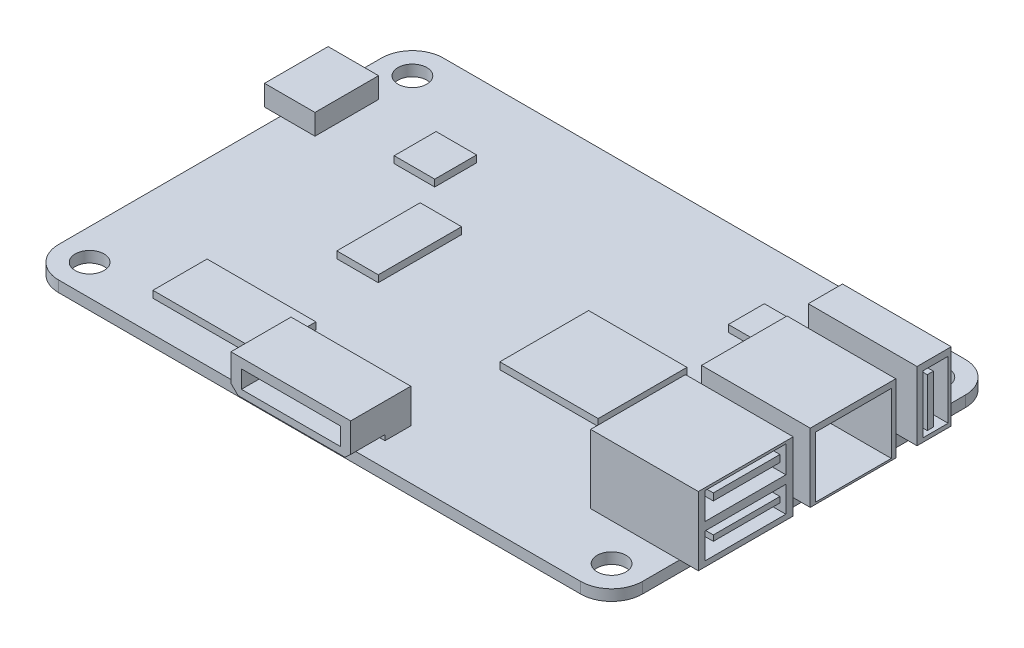
SolidWorks part; units mm, degrees
ref_plane "前视基准面" through (0, 0, 0) normal (0, 0, 1) x (1, 0, 0)
ref_plane "上视基准面" through (0, 0, 0) normal (0, 1, 0) x (1, 0, 0)
ref_plane "右视基准面" through (0, 0, 0) normal (1, 0, 0) x (0, 0, -1)
sketch "草图1" plane through (0, 0, 0) normal (0, 1, 0) x (1, 0, 0)
  line L1 (-38, -28) -> (38, -28)
  line L2 (-42.5, -23.5) -> (-42.5, 23.5)
  line L3 (-38, 28) -> (38, 28)
  line L4 (42.5, -23.5) -> (42.5, 23.5)
  line L5 (-42.5, -28) -> (42.5, 28) construction
  line L6 (-42.5, 28) -> (42.5, -28) construction
  arc A0 (-42.5, -23.5) -> (-38, -28) centre (-38, -23.5) ccw
  arc A1 (42.5, -23.5) -> (38, -28) centre (38, -23.5) cw
  arc A2 (38, 28) -> (42.5, 23.5) centre (38, 23.5) cw
  arc A3 (-38, 28) -> (-42.5, 23.5) centre (-38, 23.5) ccw
  circle A4 centre (-38, 23.5) radius 2.1
  circle A5 centre (38, 23.5) radius 2.1
  circle A6 centre (38, -23.5) radius 2.1
  circle A7 centre (-38, -23.5) radius 2.1
  point P0 (0, 0)
  dimension "D3" = 76
  dimension "D4" = 4.2
  dimension "D5" = 56
  dimension "D1" = 85
  dimension "D2" = 47
extrude "凸台-拉伸1" add sketch "草图1" along normal blind 1.6
sketch "草图2" plane through (0, 1.6, 0) normal (0, 1, 0) x (1, 0, 0)
  line L1 (29.5545, 10.4948) -> (45.3855, 10.4948)
  line L2 (29.5545, 10.4948) -> (29.5545, -1.9603)
  line L3 (29.5545, -1.9603) -> (45.3855, -1.9603)
  line L4 (45.3855, 10.4948) -> (45.3855, -1.9603)
  line L5 (29.5545, -4.2928) -> (45.2347, -4.2928)
  line L6 (29.5545, -4.2928) -> (29.5545, -18.0996)
  line L7 (29.5545, -18.0996) -> (45.2347, -18.0996)
  line L8 (45.2347, -4.2928) -> (45.2347, -18.0996)
  line L9 (29.5545, 13.5881) -> (45.3855, 13.5881)
  line L10 (29.5545, 13.5881) -> (29.5545, 18.5676)
  line L11 (29.5545, 18.5676) -> (45.3855, 18.5676)
  line L12 (45.3855, 13.5881) -> (45.3855, 18.5676)
extrude "凸台-拉伸2" add sketch "草图2" along normal blind 10
sketch "草图4" plane through (45.2347, 0, 0) normal (1, 0, 0) x (0, 0, -1)
  line L1 (-17.1075, 11.2377) -> (-5.3545, 11.2377)
  line L2 (-17.1075, 11.2377) -> (-17.1075, 7.3383)
  line L3 (-17.1075, 7.3383) -> (-5.3545, 7.3383)
  line L4 (-5.3545, 11.2377) -> (-5.3545, 7.3383)
  line L5 (-17.1075, 6.1453) -> (-5.3646, 6.1453)
  line L6 (-17.1075, 6.1453) -> (-17.1075, 2.3739)
  line L7 (-17.1075, 2.3739) -> (-5.3646, 2.3739)
  line L8 (-5.3646, 6.1453) -> (-5.3646, 2.3739)
  line L9 (-15.9177, 10.3356) -> (-6.2275, 10.3356)
  line L10 (-15.9177, 10.3356) -> (-15.9177, 9.3171)
  line L11 (-15.9177, 9.3171) -> (-6.2275, 9.3171)
  line L12 (-6.2275, 10.3356) -> (-6.2275, 9.3171)
  line L13 (-15.9177, 5.0395) -> (-6.2275, 5.0395)
  line L14 (-15.9177, 5.0395) -> (-15.9177, 4.2247)
  line L15 (-15.9177, 4.2247) -> (-6.2275, 4.2247)
  line L16 (-6.2275, 5.0395) -> (-6.2275, 4.2247)
extrude "切除-拉伸1" cut sketch "草图4" against normal blind 10
sketch "草图5" plane through (45.3855, 0, 0) normal (1, 0, 0) x (0, 0, -1)
  line L1 (-1.1827, 10.7083) -> (9.8421, 10.7083)
  line L2 (-1.1827, 10.7083) -> (-1.1827, 1.88)
  line L3 (-1.1827, 1.88) -> (9.8421, 1.88)
  line L4 (9.8421, 10.7083) -> (9.8421, 1.88)
extrude "切除-拉伸3" cut sketch "草图5" against normal blind 10
sketch "草图6" plane through (45.3855, 0, 0) normal (1, 0, 0) x (0, 0, -1)
  line L1 (14.4463, 10.6239) -> (18.1213, 10.6239)
  line L2 (14.4463, 10.6239) -> (14.4463, 2.1757)
  line L3 (14.4463, 2.1757) -> (18.1213, 2.1757)
  line L4 (18.1213, 10.6239) -> (18.1213, 2.1757)
  line L5 (15.0799, 9.8213) -> (15.967, 9.8213)
  line L6 (15.0799, 9.8213) -> (15.0799, 2.7671)
  line L7 (15.0799, 2.7671) -> (15.967, 2.7671)
  line L8 (15.967, 9.8213) -> (15.967, 2.7671)
extrude "切除-拉伸4" cut sketch "草图6" against normal blind 10
sketch "草图7" plane through (0, 1.6, 0) normal (0, 1, 0) x (1, 0, 0)
  line L1 (5.4203, 5.7343) -> (19.7393, 5.7343)
  line L2 (5.4203, 5.7343) -> (5.4203, -7.1927)
  line L3 (5.4203, -7.1927) -> (19.7393, -7.1927)
  line L4 (19.7393, 5.7343) -> (19.7393, -7.1927)
  line L5 (-20.4336, 7.0601) -> (-14.401, 7.0601)
  line L6 (-20.4336, 7.0601) -> (-20.4336, -5.0713)
  line L7 (-20.4336, -5.0713) -> (-14.401, -5.0713)
  line L8 (-14.401, 7.0601) -> (-14.401, -5.0713)
  line L9 (-28.256, 17.2028) -> (-22.356, 17.2028)
  line L10 (-28.256, 17.2028) -> (-28.256, 11.1039)
  line L11 (-28.256, 11.1039) -> (-22.356, 11.1039)
  line L12 (-22.356, 17.2028) -> (-22.356, 11.1039)
  line L13 (17.3528, 19.3904) -> (22.6562, 19.3904)
  line L14 (17.3528, 19.3904) -> (17.3528, 14.1533)
  line L15 (17.3528, 14.1533) -> (22.6562, 14.1533)
  line L16 (22.6562, 19.3904) -> (22.6562, 14.1533)
  line L17 (-28.8526, -15.5455) -> (-13.0089, -15.5455)
  line L18 (-28.8526, -15.5455) -> (-28.8526, -23.4342)
  line L19 (-28.8526, -23.4342) -> (-13.0089, -23.4342)
  line L20 (-13.0089, -15.5455) -> (-13.0089, -23.4342)
extrude "凸台-拉伸3" add sketch "草图7" along normal blind 1
sketch "草图8" plane through (0, 1.6, 0) normal (0, 1, 0) x (1, 0, 0)
  line L1 (-11.4179, -20.7545) -> (6.0169, -20.7545)
  line L2 (-11.4179, -20.7545) -> (-11.4179, -29.5051)
  line L3 (-11.4179, -29.5051) -> (6.0169, -29.5051)
  line L4 (6.0169, -20.7545) -> (6.0169, -29.5051)
  point P4 (6.0169, -29.5051)
extrude "凸台-拉伸4" add sketch "草图8" along normal blind 5
sketch "草图9" plane through (0, 0, 29.5051) normal (0, 0, 1) x (1, 0, 0)
  line L0 (-11.4179, 1.6) -> (-11.4179, 2.6275)
  line L1 (-9.8931, 5.2129) -> (4.5585, 5.2129)
  line L2 (-9.8931, 5.2129) -> (-9.8931, 2.6275)
  line L3 (-9.8931, 2.6275) -> (4.5585, 2.6275)
  line L4 (4.5585, 5.2129) -> (4.5585, 2.6275)
  line L5 (-11.4179, 6.6) -> (-11.4179, 1.6) construction
  line L6 (-11.4179, 2.6275) -> (-10.3903, 1.6)
  line L7 (-11.4179, 1.6) -> (6.0169, 1.6) construction
  line L8 (-10.3903, 1.6) -> (-11.4179, 1.6)
  line L9 (6.0169, 1.6) -> (6.0169, 2.3706)
  line L10 (6.0169, 6.6) -> (6.0169, 1.6) construction
  line L11 (6.0169, 2.3706) -> (5.1927, 1.6)
  line L12 (5.1927, 1.6) -> (6.0169, 1.6)
  point P17 (6.0169, 2.3706)
extrude "切除-拉伸5" cut sketch "草图9" against normal blind 5
sketch "草图10" plane through (0, 1.6, 0) normal (0, 1, 0) x (1, 0, 0)
  line L1 (-37.4838, 18.0571) -> (-44.8296, 18.0571)
  line L2 (-37.4838, 18.0571) -> (-37.4838, 8.795)
  line L3 (-37.4838, 8.795) -> (-44.8296, 8.795)
  line L4 (-44.8296, 18.0571) -> (-44.8296, 8.795)
extrude "凸台-拉伸5" add sketch "草图10" along normal blind 3
sketch "草图11" plane through (-44.8296, 0, 0) normal (-1, 0, 0) x (0, 0, 1)
  line L1 (-17.283, 3.7729) -> (-9.5133, 3.7729)
  line L2 (-17.283, 3.7729) -> (-17.283, 2.0609)
  line L3 (-17.283, 2.0609) -> (-9.5133, 2.0609)
  line L4 (-9.5133, 3.7729) -> (-9.5133, 2.0609)
extrude "切除-拉伸6" cut sketch "草图11" against normal blind 3
